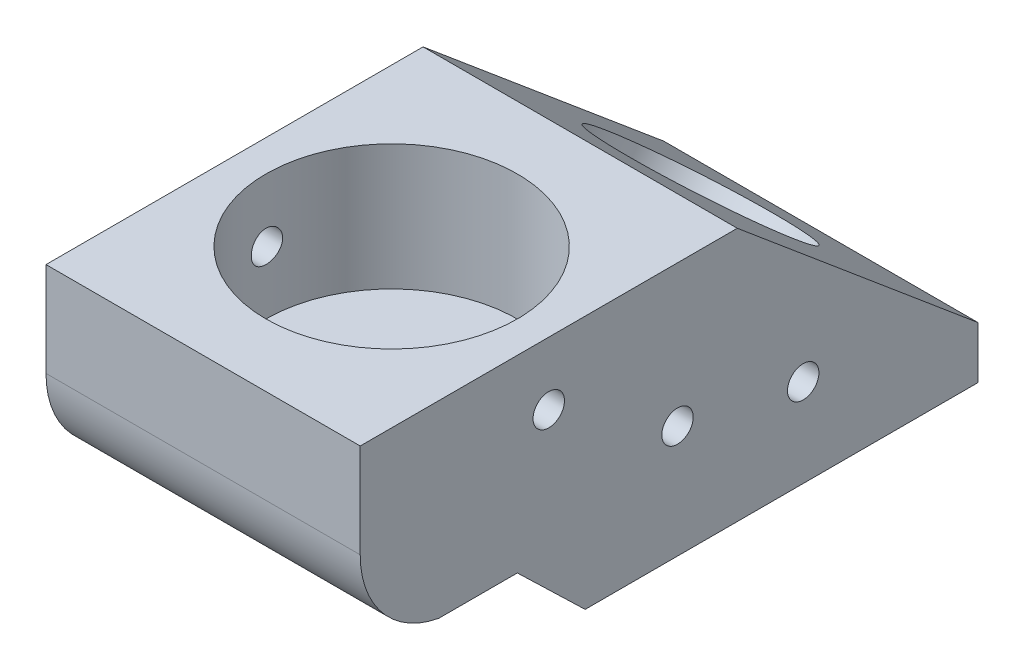
SolidWorks part; units mm, degrees
ref_plane "Front Plane" through (0, 0, 0) normal (0, 0, 1) x (1, 0, 0)
ref_plane "Top Plane" through (0, 0, 0) normal (0, 1, 0) x (1, 0, 0)
ref_plane "Right Plane" through (0, 0, 0) normal (1, 0, 0) x (0, 0, -1)
sketch "Sketch2" plane through (0, 0, 0) normal (1, 0, 0) x (0, 0, -1)
  line L0 (0, 0) -> (-120, 0)
  line L5 (-120, 0) -> (-120, -60)
  line L6 (-48.4141, -80.8339) -> (29.789, -80.8339)
  line L8 (76.6044, -64.2788) -> (0, 0)
  line L10 (-120, -60) -> (-70, -60)
  line L11 (-70, -60) -> (-48.4141, -80.8339)
  line L12 (76.6044, -64.2788) -> (76.6044, -80.8339)
  line L13 (29.789, -80.8339) -> (76.6044, -80.8339)
  point P0 (0, 0)
  dimension "D5" = 50
  dimension "D1" = 120
  dimension "D2" = 140
  dimension "D3" = 100
  dimension "D4" = 60
  dimension "D6" = 30
extrude "Boss-Extrude1" add sketch "Sketch2" against normal blind 100
sketch "Sketch3" plane through (0, 0, 0) normal (0, 1, 0) x (1, 0, 0)
  circle A1 centre (-50, -60) radius 40
  dimension "D1" = 80
extrude "Cut-Extrude1" cut sketch "Sketch3" against normal blind 40
sketch "Sketch4" plane through (0, 0, 0) normal (0, 0.766, -0.6428) x (1, 0, 0)
  circle A1 centre (-50, 50) radius 30
  dimension "D1" = 60
extrude "Cut-Extrude2" cut sketch "Sketch4" against normal through all
sketch "Sketch5" plane through (0, 0, 0) normal (1, 0, 0) x (0, 0, -1)
  circle A0 centre (20.9761, -52.7879) radius 5
  dimension "D1" = 10
extrude "Cut-Extrude3" cut sketch "Sketch5" against normal through all
sketch "Sketch6" plane through (0, 0, 0) normal (1, 0, 0) x (0, 0, -1)
  line L0 (0, 0) -> (-120, 0) construction
  circle A0 centre (-19.0239, -45) radius 5
  circle A1 centre (20.9761, -52.7879) radius 5 construction
  dimension "D1" = 10
  dimension "D2" = 40
  dimension "D3" = 45
extrude "Cut-Extrude4" cut sketch "Sketch6" against normal through all
sketch "Sketch7" plane through (0, 0, 0) normal (1, 0, 0) x (0, 0, -1)
  line L0 (-20, 0) -> (-100, 0) construction
  circle A0 centre (-60, -20) radius 5
  dimension "D1" = 10
  dimension "D2" = 20
extrude "Cut-Extrude5" cut sketch "Sketch7" against normal through all
sketch "Sketch8" plane through (0, 0, 0) normal (1, 0, 0) x (0, 0, -1)
  line L13 (-120, -30) -> (-120, -60)
  line L14 (-120, 0) -> (-120, -60) construction
  line L15 (-120, -60) -> (-95, -60)
  line L16 (-120, -60) -> (-70, -60) construction
  arc A5 (-120, -30) -> (-95, -60) centre (-89.5, -30) ccw
extrude "Cut-Extrude7" cut sketch "Sketch8" against normal through all
